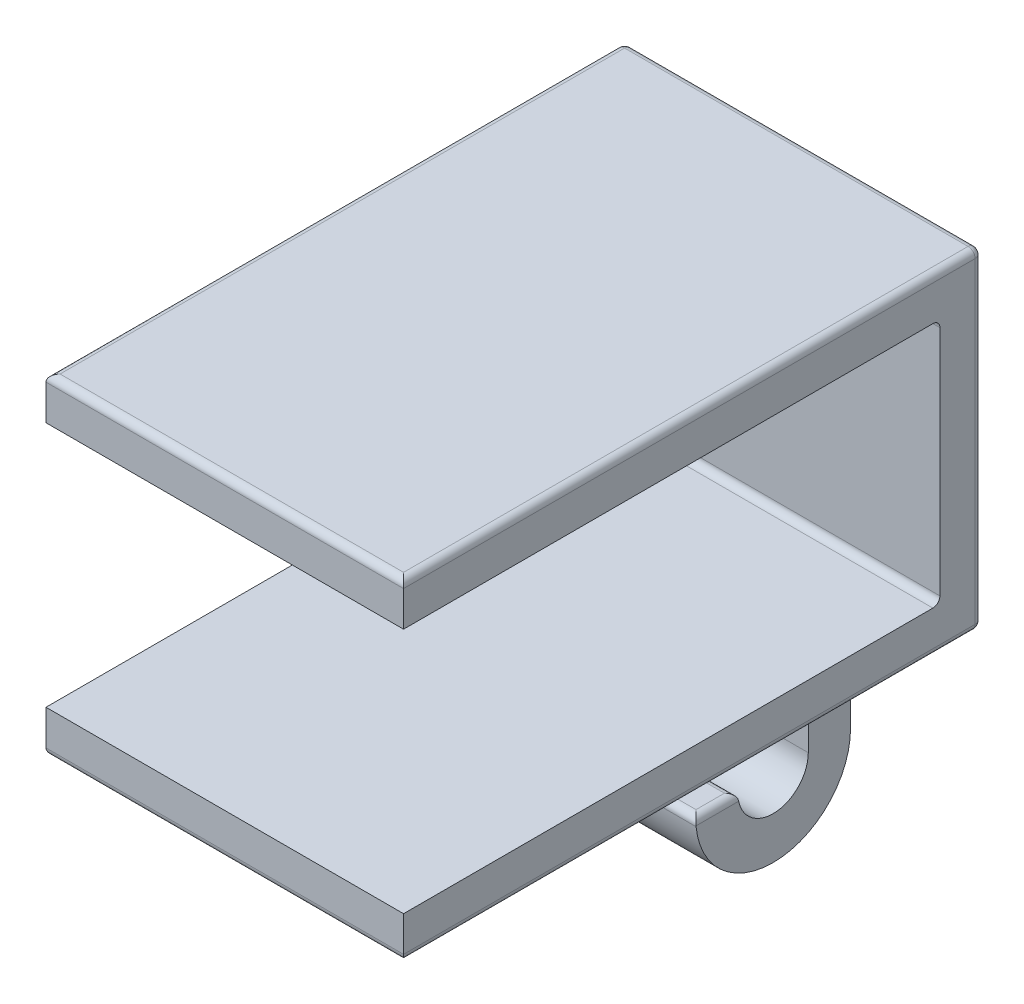
SolidWorks part; units mm, degrees
ref_plane "Front Plane" through (0, 0, 0) normal (0, 0, 1) x (1, 0, 0)
ref_plane "Top Plane" through (0, 0, 0) normal (0, 1, 0) x (1, 0, 0)
ref_plane "Right Plane" through (0, 0, 0) normal (1, 0, 0) x (0, 0, -1)
sketch "Sketch1" plane through (0, 0, 0) normal (1, 0, 0) x (0, 0, -1)
  line L0 (0, 0) -> (38.1, 0)
  line L1 (38.1, 0) -> (38.1, -17.5)
  line L2 (38.1, -17.5) -> (0, -17.5)
  line L3 (0, -17.5) -> (0, -20.5)
  line L4 (0, -20.5) -> (41.1, -20.5)
  line L5 (41.1, -20.5) -> (41.1, 3)
  line L6 (41.1, 3) -> (0, 3)
  line L7 (0, 3) -> (0, 0)
  point P3 (40.9915, -8.5851)
  dimension "D5" = 17.5
  dimension "D1" = 3
  dimension "D2" = 3
  dimension "D3" = 3
  dimension "D4" = 38.1
extrude "Boss-Extrude1" add sketch "Sketch1" along normal blind 25.4
sketch "Sketch7" plane through (0, 0, 0) normal (-1, 0, 0) x (0, 0, 1)
  line L0 (-38.1, -20.5) -> (-38.1, -28.3363)
  line L2 (-27.1, -28.3363) -> (-30.1, -28.3363)
  line L3 (-35.1, -28.3218) -> (-35.1, -20.5)
  line L4 (0, -20.5) -> (-41.1, -20.5) construction
  line L5 (-35.1, -20.5) -> (-38.1, -20.5)
  arc A0 (-38.1, -28.3363) -> (-27.1, -28.3363) centre (-32.6, -28.3363) ccw
  arc A1 (-30.1, -28.3363) -> (-35.1, -28.3218) centre (-32.6, -28.3218) cw
  dimension "D2" = 5.5
  dimension "D1" = 3
  dimension "D3" = 3
extrude "Boss-Extrude3" add sketch "Sketch7" against normal blind 25.4
sketch "Sketch8" plane through (0, 0, 0) normal (-1, 0, 0) x (0, 0, 1)
  line L0 (-35.1, -20.5) -> (-38.1, -20.5)
  line L1 (-38.1, -20.5) -> (-38.1, -28.3363)
  line L2 (-35.1, -20.5) -> (-35.1, -28.3218)
  line L3 (-35.1, -28.3218) -> (-35.1, -20.5) construction
  line L4 (-30.1, -28.3363) -> (-27.1, -28.3363)
  arc A0 (-35.1, -28.3218) -> (-30.1, -28.3363) centre (-32.6, -28.3218) ccw construction
  arc A1 (-38.1, -28.3363) -> (-27.1, -28.3363) centre (-32.6, -28.3363) ccw
  arc A2 (-30.1, -28.3363) -> (-35.1, -28.3218) centre (-32.6, -28.3218) cw
extrude "Cut-Extrude5" cut sketch "Sketch8" against normal blind 6.35
sketch "Sketch9" plane through (25.4, 0, 0) normal (1, 0, 0) x (0, 0, -1)
  line L0 (35.1, -20.5) -> (38.1, -20.5)
  line L1 (38.1, -20.5) -> (38.1, -28.3363)
  line L2 (35.1, -20.5) -> (35.1, -28.3218)
  line L3 (27.1, -28.3363) -> (30.1, -28.3363)
  arc A0 (38.1, -28.3363) -> (27.1, -28.3363) centre (32.6, -28.3363) cw
  arc A1 (35.1, -28.3218) -> (30.1, -28.3363) centre (32.6, -28.3218) cw
extrude "Cut-Extrude6" cut sketch "Sketch9" against normal blind 6.35
fillet "Fillet1" radius 2.5 2 edges at (12.7, -20.5, -38.1) (12.7, -20.5, -35.1)
fillet "Fillet2" radius 2.5 2 edges at (6.35, -20.5, -36.6) (19.05, -20.5, -36.6)
fillet "Fillet3" radius 0.5 10 edges at (12.7, 3, 0) (12.7, -20.5, 0) (25.4, -20.5, -20.55) (25.4, -8.75, -41.1) (25.4, 3, -20.55) (12.7, 3, -41.1) (0, 3, -20.55) (0, -8.75, -41.1) (0, -20.5, -20.55) (12.7, -20.5, -41.1)
fillet "Fillet4" radius 0.5 4 edges at (19.05, -28.3363, -28.6) (6.35, -28.3363, -28.6) (12.7, -28.3363, -30.1) (12.7, -28.3363, -27.1)
fillet "Fillet5" radius 0.5 2 edges at (12.7, 0, -38.1) (12.7, -17.5, -38.1)
